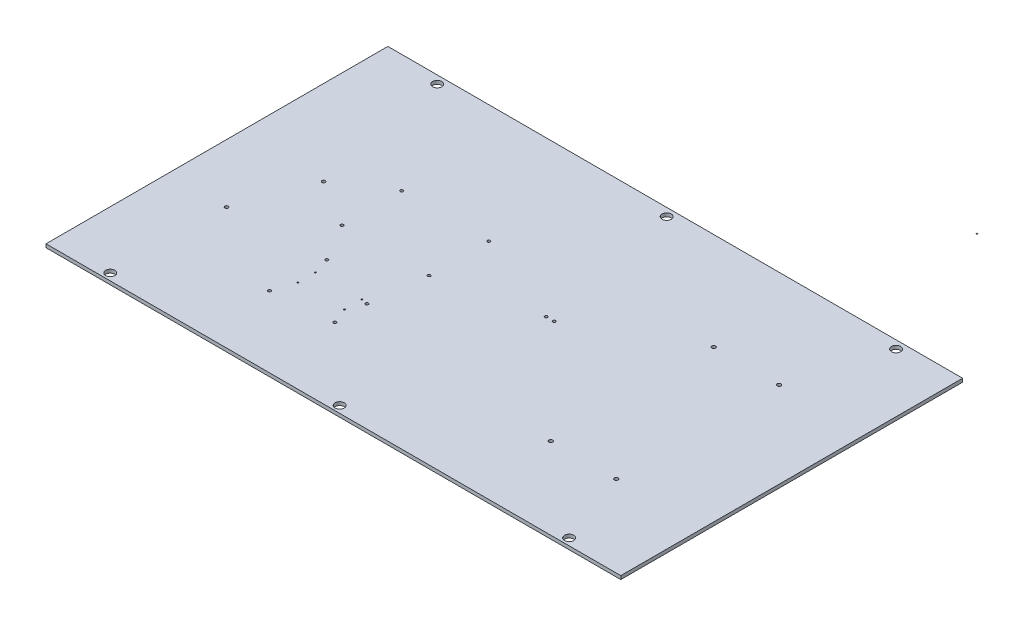
SolidWorks part; units mm, degrees
ref_plane "Front Plane" through (0, 0, 0) normal (0, 0, 1) x (1, 0, 0)
ref_plane "Top Plane" through (0, 0, 0) normal (0, 1, 0) x (1, 0, 0)
ref_plane "Right Plane" through (0, 0, 0) normal (1, 0, 0) x (0, 0, -1)
sketch "Sketch1" plane through (0, 0, 0) normal (0, 1, 0) x (1, 0, 0)
  line L1 (200, 250) -> (200.001, 250)
  line L2 (200, 250) -> (200, 249.999)
  line L3 (200, 249.999) -> (200.001, 249.999)
  line L4 (200.001, 250) -> (200.001, 249.999)
  dimension "D1" = 0.001
  dimension "D2" = 0.001
extrude "Extrude-Thin5" add sketch "Sketch1" along normal blind 0.01 thin thin type one direction wall 0.5
sketch "Sketch2" plane through (0, 0, 0) normal (0, 1, 0) x (1, 0, 0)
  line L1 (-198.0881, 134.7025) -> (302.9119, 134.7025)
  line L2 (-198.0881, 134.7025) -> (-198.0881, -163.2975)
  line L3 (-198.0881, -163.2975) -> (302.9119, -163.2975)
  line L4 (302.9119, 134.7025) -> (302.9119, -163.2975)
  dimension "D1" = 501
  dimension "D2" = 298
extrude "Boss-Extrude2" add sketch "Sketch2" against normal blind 3
hole_wizard "M3x0.5 Tapped Hole3" positions "Sketch34" profile "Sketch35" tap size "M3x0.5" standard "ANSI Metric" end condition through all
sketch "Sketch34" plane through (0, 0, 0) normal (0, 1, 0) x (1, 0, 0)
  line L0 (-198.0881, 134.7025) -> (-198.0881, -163.2975) construction
  line L1 (302.9119, 134.7025) -> (-198.0881, 134.7025) construction
  point P0 (-83.0881, 31.7025)
  point P2 (-7.0881, 31.7025)
  point P4 (-7.0881, -20.2975)
  point P6 (-83.0881, -20.2975)
  dimension "D1" = 115
  dimension "D2" = 103
  dimension "D3" = 76
  dimension "D4" = 0
  dimension "D5" = 0
  dimension "D6" = 0
  dimension "D7" = 52
  dimension "D8" = 52
sketch "Sketch35" plane through (-83.0881, 0, -31.7025) normal (1, 0, 0) x (0, 0, 1)
  line L0 (0, 0) -> (0, 3)
  line L1 (0, 3) -> (1.25, 3)
  line L2 (1.25, 3) -> (1.25, 0)
  line L5 (1.25, 0) -> (0, 0)
  line L11 (0, -6.35) -> (0, 107.95) construction
  dimension "Thru Tap Drill Dia." = 2.5
  dimension "Thru Tap Drill Depth" = 3
cosmetic thread "Hole Thread24" parameters "D2"=3
cosmetic thread "Hole Thread25" parameters "D2"=3
cosmetic thread "Hole Thread26" parameters "D2"=3
cosmetic thread "Hole Thread27" parameters "D2"=3
hole_wizard "M3x0.5 Tapped Hole2" positions "Sketch36" profile "Sketch37" tap size "M3x0.5" standard "ANSI Metric" end condition through all
sketch "Sketch36" plane through (0, 0, 0) normal (0, 1, 0) x (1, 0, 0)
  line L0 (-198.0881, 134.7025) -> (-198.0881, -163.2975) construction
  line L3 (-198.0881, -163.2975) -> (302.9119, -163.2975) construction
  point P0 (-63.5881, -53.0374)
  point P2 (-12.8881, -68.7374)
  point P4 (-65.2881, -101.2975)
  point P6 (-12.8881, -96.6774)
  point P15 (0, 0)
  dimension "D1" = 134.5
  dimension "D2" = 62
  dimension "D3" = 1.7
  dimension "D4" = 48.29
  dimension "D5" = 15.7
  dimension "D6" = 50.7
  dimension "D7" = 0
  dimension "D8" = 27.94
sketch "Sketch37" plane through (-63.5881, 0, 53.0374) normal (1, 0, 0) x (0, 0, 1)
  line L0 (0, 0) -> (0, 3)
  line L1 (0, 3) -> (1.25, 3)
  line L2 (1.25, 3) -> (1.25, 0)
  line L5 (1.25, 0) -> (0, 0)
  line L11 (0, -6.35) -> (0, 107.95) construction
  dimension "Thru Tap Drill Dia." = 2.5
  dimension "Thru Tap Drill Depth" = 3
cosmetic thread "Hole Thread28" parameters "D2"=3
cosmetic thread "Hole Thread29" parameters "D2"=3
cosmetic thread "Hole Thread30" parameters "D2"=3
cosmetic thread "Hole Thread31" parameters "D2"=3
hole_wizard "M4x0.7 Tapped Hole1" positions "Sketch38" profile "Sketch39" tap size "M4x0.7" standard "ANSI Metric" end condition through all
sketch "Sketch38" plane through (0, 0, 0) normal (0, 1, 0) x (1, 0, 0)
  line L0 (302.9119, -163.2975) -> (302.9119, 134.7025) construction
  line L1 (302.9119, 134.7025) -> (-198.0881, 134.7025) construction
  point P0 (227.9119, 49.7025)
  point P2 (170.9119, 49.7025)
  point P4 (170.9119, -92.2975)
  point P6 (227.9119, -92.2975)
  dimension "D1" = 75
  dimension "D2" = 85
  dimension "D3" = 142
  dimension "D4" = 57
  dimension "D5" = 0
  dimension "D6" = 0
  dimension "D7" = 0
  dimension "D8" = 0
sketch "Sketch39" plane through (227.9119, 0, -49.7025) normal (1, 0, 0) x (0, 0, 1)
  line L0 (0, 0) -> (0, 3)
  line L1 (0, 3) -> (1.65, 3)
  line L2 (1.65, 3) -> (1.65, 0)
  line L5 (1.65, 0) -> (0, 0)
  line L11 (0, -6.35) -> (0, 107.95) construction
  dimension "Thru Tap Drill Dia." = 3.3
  dimension "Thru Tap Drill Depth" = 3
cosmetic thread "Hole Thread16" parameters "D2"=4
cosmetic thread "Hole Thread17" parameters "D2"=4
cosmetic thread "Hole Thread18" parameters "D2"=4
cosmetic thread "Hole Thread19" parameters "D2"=4
hole_wizard "M1.6x0.35 Tapped Hole1" positions "3DSketch1" profile "Sketch40" tap size "M1.6x0.35" standard "ANSI Metric" end condition through all
sketch3d "3DSketch1"
  line L1 (-198.0881, 0, 163.2975) -> (302.9119, 0, 163.2975) construction
  line L3 (-198.0881, 0, 163.2975) -> (302.9119, 0, 163.2975) construction
  line L5 (-198.0881, 0, -134.7025) -> (-198.0881, 0, 163.2975) construction
  point P0 (-18.4481, 0, 82.7975)
  point P2 (-59.0881, 0, 82.7975)
  point P4 (-59.0881, 0, 67.5575)
  point P6 (-18.4481, 0, 67.5575)
  dimension "D1" = 139
  dimension "D2" = 15.24
  dimension "D3" = 80.5
  dimension "D4" = 40.64
  dimension "D5" = 40.64
  dimension "D6" = 15.24
  dimension "D7" = 139
  dimension "D8" = 80.5
sketch "Sketch40" plane through (-18.4481, 0, 82.7975) normal (1, 0, 0) x (0, 0, 1)
  line L0 (0, 0) -> (0, 3)
  line L1 (0, 3) -> (0.625, 3)
  line L2 (0.625, 3) -> (0.625, 0)
  line L5 (0.625, 0) -> (0, 0)
  line L11 (0, -6.35) -> (0, 107.95) construction
  dimension "Thru Tap Drill Dia." = 1.25
  dimension "Thru Tap Drill Depth" = 3
cosmetic thread "Hole Thread20" parameters "D2"=1.6
cosmetic thread "Hole Thread21" parameters "D2"=1.6
cosmetic thread "Hole Thread22" parameters "D2"=1.6
cosmetic thread "Hole Thread23" parameters "D2"=1.6
hole_wizard "M3x0.5 Tapped Hole1" positions "Sketch41" profile "Sketch42" tap size "M3x0.5" standard "ANSI Metric" end condition through all
sketch "Sketch41" plane through (0, 0, 0) normal (0, 1, 0) x (1, 0, 0)
  line L0 (302.9119, 134.7025) -> (-198.0881, 134.7025) construction
  line L1 (302.9119, -163.2975) -> (302.9119, 134.7025) construction
  point P0 (81.9119, -0.2975)
  point P2 (74.9119, -0.2975)
  dimension "D1" = 135
  dimension "D2" = 228
  dimension "D3" = 135
sketch "Sketch42" plane through (81.9119, 0, 0.2975) normal (1, 0, 0) x (0, 0, 1)
  line L0 (0, 0) -> (0, 3)
  line L1 (0, 3) -> (1.25, 3)
  line L2 (1.25, 3) -> (1.25, 0)
  line L5 (1.25, 0) -> (0, 0)
  line L11 (0, -6.35) -> (0, 107.95) construction
  dimension "Thru Tap Drill Dia." = 2.5
  dimension "Thru Tap Drill Depth" = 3
cosmetic thread "Hole Thread14" parameters "D2"=3
cosmetic thread "Hole Thread15" parameters "D2"=3
hole_wizard "M3.5x0.6 Tapped Hole1" positions "Sketch48" profile "Sketch49" tap size "M3.5x0.6" standard "ANSI Metric" end condition through all
sketch "Sketch48" plane through (0, 0, 0) normal (0, 1, 0) x (1, 0, 0)
  line L0 (302.9119, 134.7025) -> (-198.0881, 134.7025) construction
  line L2 (-198.0881, 134.7025) -> (-198.0881, -163.2975) construction
  point P0 (-124.0881, 4.7025)
  point P2 (-147.0881, -56.8975)
  dimension "D1" = 130
  dimension "D2" = 74
  dimension "D3" = 23
  dimension "D4" = 61.6
sketch "Sketch49" plane through (-124.0881, 0, -4.7025) normal (1, 0, 0) x (0, 0, 1)
  line L0 (0, 0) -> (0, 3)
  line L1 (0, 3) -> (1.45, 3)
  line L2 (1.45, 3) -> (1.45, 0)
  line L5 (1.45, 0) -> (0, 0)
  line L11 (0, -6.35) -> (0, 107.95) construction
  dimension "Thru Tap Drill Dia." = 2.9
  dimension "Thru Tap Drill Depth" = 3
cosmetic thread "Hole Thread2" parameters "D2"=3.5
cosmetic thread "Hole Thread3" parameters "D2"=3.5
hole_wizard "Ø8.0mm Dowel Hole1" positions "Sketch54" profile "Sketch55" hole size "Ø8.0" standard "ANSI Metric" end condition through all
sketch "Sketch54" plane through (0, -3, 0) normal (0, -1, 0) x (-1, 0, 0)
  line L0 (198.0881, -163.2975) -> (-302.9119, -163.2975) construction
  line L1 (198.0881, 134.7025) -> (198.0881, -163.2975) construction
  line L2 (-302.9119, 134.7025) -> (198.0881, 134.7025) construction
  point P0 (148.0881, -157.2975)
  point P1 (-51.9119, -157.2975)
  point P3 (-251.9119, -157.2975)
  point P5 (-251.9119, 127.7025)
  point P7 (-51.9119, 127.7025)
  point P9 (148.0881, 127.7025)
  dimension "D1" = 6
  dimension "D2" = 6
  dimension "D3" = 6
  dimension "D4" = 50
  dimension "D5" = 200
  dimension "D6" = 200
  dimension "D7" = 50
  dimension "D8" = 7
  dimension "D9" = 7
  dimension "D10" = 200
  dimension "D11" = 200
  dimension "D12" = 7
sketch "Sketch55" plane through (-148.0881, -3, 157.2975) normal (1, 0, 0) x (0, 0, -1)
  line L0 (0, 0) -> (0, 3.01)
  line L1 (0, 3.01) -> (4, 3.01)
  line L2 (4, 3.01) -> (4, 0)
  line L5 (4, 0) -> (0, 0)
  line L11 (0, -6.35) -> (0, 107.95) construction
  dimension "Thru Hole Dia." = 8
  dimension "Thru Hole Depth" = 3.01
